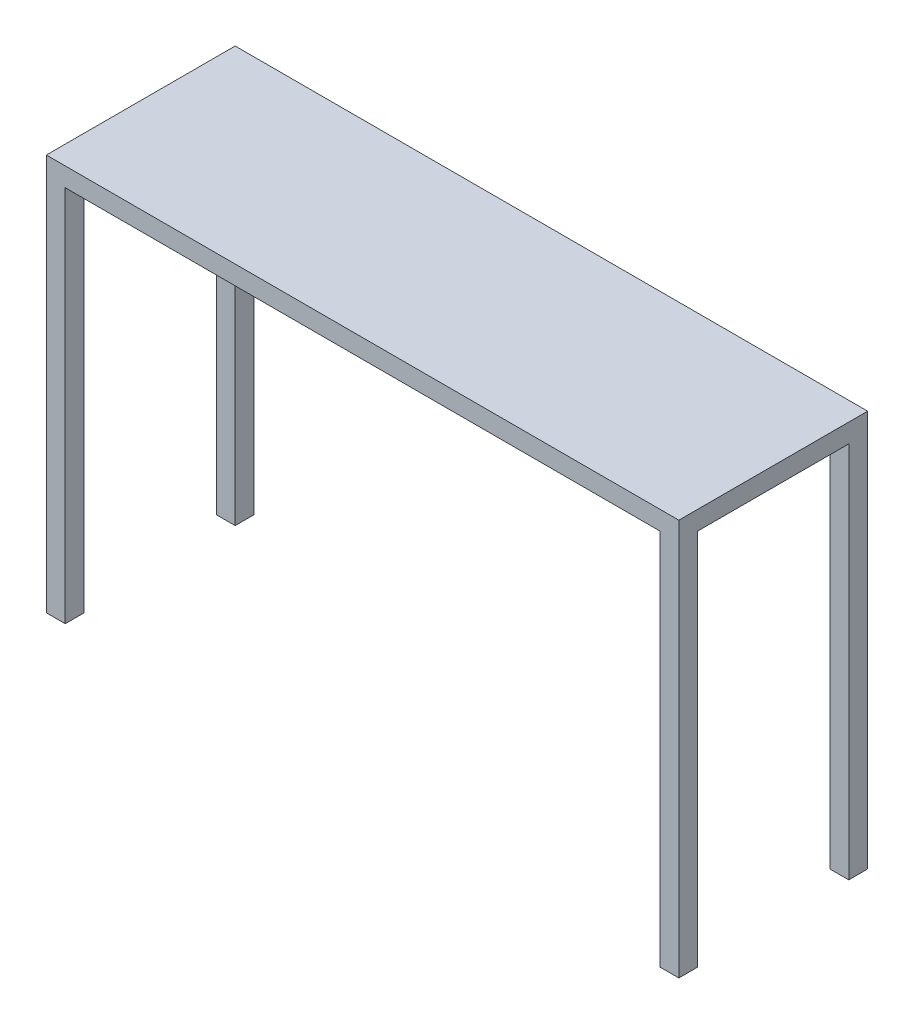
SolidWorks part; units mm, degrees
material "Maple"
ref_plane "Front" through (0, 0, 0) normal (0, 0, 1) x (1, 0, 0)
ref_plane "Top" through (0, 0, 0) normal (0, 1, 0) x (1, 0, 0)
ref_plane "Right" through (0, 0, 0) normal (1, 0, 0) x (0, 0, -1)
sketch "Sketch1" plane through (0, 0, 0) normal (0, 1, 0) x (1, 0, 0)
  line L1 (-850.9, 254) -> (850.9, 254)
  line L2 (-850.9, 254) -> (-850.9, -254)
  line L3 (-850.9, -254) -> (850.9, -254)
  line L4 (850.9, 254) -> (850.9, -254)
  line L5 (-850.9, 254) -> (850.9, -254) construction
  line L6 (-850.9, -254) -> (850.9, 254) construction
  point P0 (0, 0)
  dimension "D1" = 1701.8
  dimension "D2" = 508
extrude "Boss-Extrude1" add sketch "Sketch1" along normal blind 50.8
sketch "Sketch2" plane through (0, 0, 0) normal (0, -1, 0) x (1, 0, 0)
  line L1 (-850.9, 254) -> (-800.1, 254)
  line L2 (-850.9, 254) -> (-850.9, 203.2)
  line L3 (-850.9, 203.2) -> (-800.1, 203.2)
  line L4 (-800.1, 254) -> (-800.1, 203.2)
  line L5 (-850.9, -254) -> (-800.1, -254)
  line L6 (-850.9, -254) -> (-850.9, -203.2)
  line L7 (-850.9, -203.2) -> (-800.1, -203.2)
  line L8 (-800.1, -254) -> (-800.1, -203.2)
  line L9 (850.9, 254) -> (800.1, 254)
  line L10 (850.9, 254) -> (850.9, 203.2)
  line L11 (850.9, 203.2) -> (800.1, 203.2)
  line L12 (800.1, 254) -> (800.1, 203.2)
  line L13 (850.9, -254) -> (800.1, -254)
  line L14 (850.9, -254) -> (850.9, -203.2)
  line L15 (850.9, -203.2) -> (800.1, -203.2)
  line L16 (800.1, -254) -> (800.1, -203.2)
  dimension "D1" = 50.8
extrude "Boss-Extrude2" add sketch "Sketch2" along normal blind 1016
